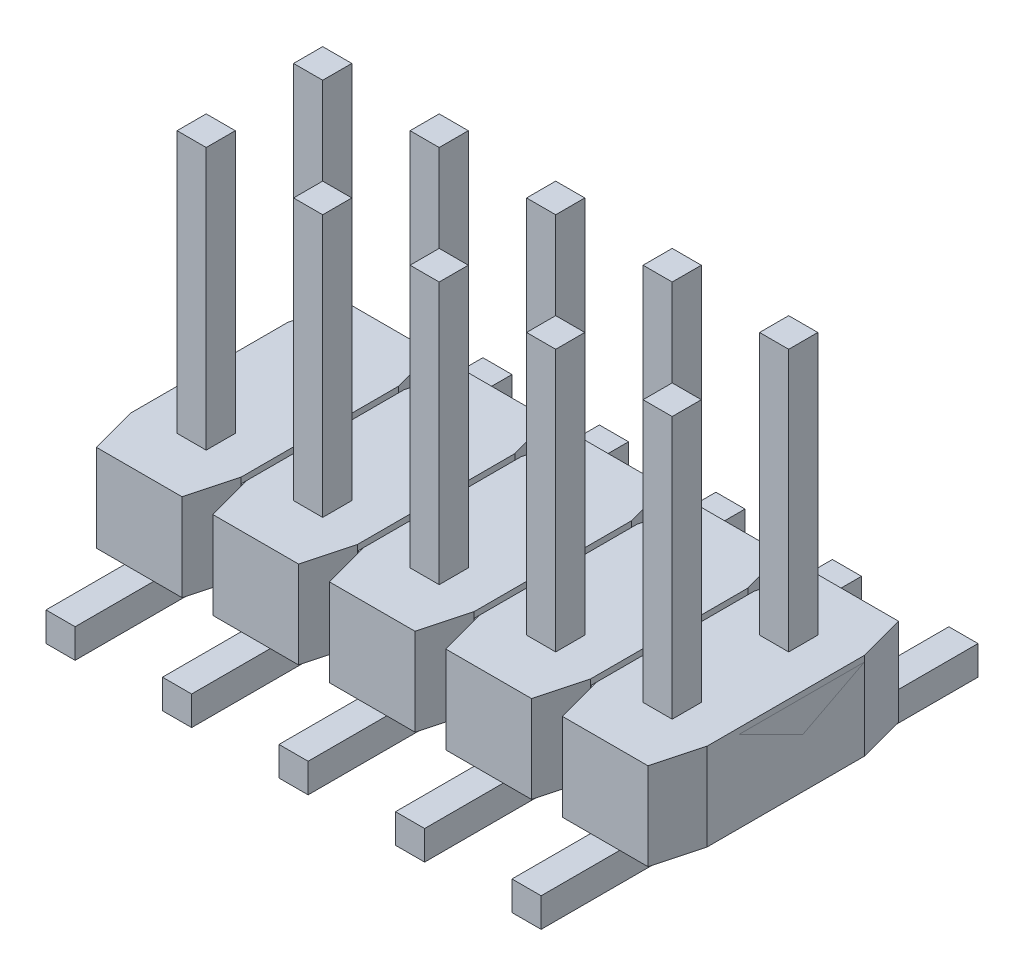
SolidWorks part; units mm, degrees
ref_plane "Alzado" through (0, 0, 0) normal (0, 0, 1) x (1, 0, 0)
ref_plane "Planta" through (0, 0, 0) normal (0, 1, 0) x (1, 0, 0)
ref_plane "Vista lateral" through (0, 0, 0) normal (1, 0, 0) x (0, 0, -1)
sketch "Croquis1" plane through (0, 0, 0) normal (0, 1, 0) x (1, 0, 0)
  line L0 (2, 0) -> (2.5, 0)
  line L1 (0, 0) -> (0.5, 0)
  line L2 (0, 0) -> (0, 0.5)
  line L3 (0, 0.5) -> (0.5, 0.5)
  line L4 (0.5, 0) -> (0.5, 0.5)
  line L5 (2, 0) -> (2, 0.5)
  line L6 (2, 0.5) -> (2.5, 0.5)
  line L7 (2.5, 0) -> (2.5, 0.5)
  line L8 (4, 0) -> (4.5, 0)
  line L9 (4, 0) -> (4, 0.5)
  line L10 (4, 0.5) -> (4.5, 0.5)
  line L11 (4.5, 0) -> (4.5, 0.5)
  line L12 (6, 0) -> (6.5, 0)
  line L13 (6, 0) -> (6, 0.5)
  line L14 (6, 0.5) -> (6.5, 0.5)
  line L15 (6.5, 0) -> (6.5, 0.5)
  line L16 (8, 0) -> (8.5, 0)
  line L17 (8, 0) -> (8, 0.5)
  line L18 (8, 0.5) -> (8.5, 0.5)
  line L19 (8.5, 0) -> (8.5, 0.5)
  line L80 (0, 2) -> (0.5, 2)
  line L81 (0, 2) -> (0, 2.5)
  line L82 (0, 2.5) -> (0.5, 2.5)
  line L83 (0.5, 2) -> (0.5, 2.5)
  line L84 (2, 2) -> (2.5, 2)
  line L85 (2, 2) -> (2, 2.5)
  line L86 (2, 2.5) -> (2.5, 2.5)
  line L87 (2.5, 2) -> (2.5, 2.5)
  line L88 (4, 2) -> (4.5, 2)
  line L89 (4, 2) -> (4, 2.5)
  line L90 (4, 2.5) -> (4.5, 2.5)
  line L91 (4.5, 2) -> (4.5, 2.5)
  line L92 (6, 2) -> (6.5, 2)
  line L93 (6, 2) -> (6, 2.5)
  line L94 (6, 2.5) -> (6.5, 2.5)
  line L95 (6.5, 2) -> (6.5, 2.5)
  line L96 (8, 2) -> (8.5, 2)
  line L97 (8, 2) -> (8, 2.5)
  line L98 (8, 2.5) -> (8.5, 2.5)
  line L99 (8.5, 2) -> (8.5, 2.5)
  line L160 (0, 0) -> (2, 0) construction
  line L161 (0, 0) -> (0, 2) construction
  dimension "D1" = 0.5
  dimension "D2" = 0.5
  dimension "D3" = 90
  dimension "D4" = 2
  dimension "D5" = 2
extrude "Extruir1" add sketch "Croquis1" along normal blind 6.5
sketch "Croquis2" plane through (0, 0, 0) normal (0, -1, 0) x (1, 0, 0)
  line L0 (2, 2.25) -> (2.5, 2.25)
  line L1 (0, 2.25) -> (0.5, 2.25)
  line L2 (0, 2.25) -> (0, -5.25)
  line L3 (0, -5.25) -> (0.5, -5.25)
  line L4 (0.5, 2.25) -> (0.5, -5.25)
  line L5 (2, 2.25) -> (2, -5.25)
  line L6 (2, -5.25) -> (2.5, -5.25)
  line L7 (2.5, 2.25) -> (2.5, -5.25)
  line L8 (4, 2.25) -> (4.5, 2.25)
  line L9 (4, 2.25) -> (4, -5.25)
  line L10 (4, -5.25) -> (4.5, -5.25)
  line L11 (4.5, 2.25) -> (4.5, -5.25)
  line L12 (6, 2.25) -> (6.5, 2.25)
  line L13 (6, 2.25) -> (6, -5.25)
  line L14 (6, -5.25) -> (6.5, -5.25)
  line L15 (6.5, 2.25) -> (6.5, -5.25)
  line L16 (8, 2.25) -> (8.5, 2.25)
  line L17 (8, 2.25) -> (8, -5.25)
  line L18 (8, -5.25) -> (8.5, -5.25)
  line L19 (8.5, 2.25) -> (8.5, -5.25)
  dimension "D1" = 7.5
  dimension "D2" = 0.5
  dimension "D3" = 2.25
  dimension "D4" = 2
extrude "Extruir2" add sketch "Croquis2" against normal blind 0.5
sketch "Croquis3" plane through (0, 0.5, 0) normal (0, 1, 0) x (-1, 0, 0)
  line L0 (-0.5, -5.25) -> (-0.5, -2.5) construction
  line L1 (-0.9856, -3.4) -> (0.4856, -3.4)
  line L2 (-1.2, -2.6) -> (-1.2, 0.1)
  line L3 (-0.9856, 0.9) -> (0.4856, 0.9)
  line L4 (0.7, -2.6) -> (0.7, 0.1)
  line L5 (0, -2.5) -> (0, -5.25) construction
  line L6 (-0.5, -2.5) -> (0, -2.5) construction
  line L7 (-0.5, 0) -> (0, 0) construction
  line L8 (-1.2, -2.6) -> (-0.9856, -3.4)
  line L9 (0.4856, -3.4) -> (0.7, -2.6)
  line L10 (0.4856, 0.9) -> (0.7, 0.1)
  line L11 (-1.2, 0.1) -> (-0.9856, 0.9)
  line L12 (-2.9856, -3.4) -> (-1.5144, -3.4)
  line L13 (-3.2, -2.6) -> (-3.2, 0.1)
  line L14 (-2.9856, 0.9) -> (-1.5144, 0.9)
  line L15 (-1.3, -2.6) -> (-1.3, 0.1)
  line L16 (-3.2, -2.6) -> (-2.9856, -3.4)
  line L17 (-1.5144, -3.4) -> (-1.3, -2.6)
  line L18 (-1.5144, 0.9) -> (-1.3, 0.1)
  line L19 (-3.2, 0.1) -> (-2.9856, 0.9)
  line L20 (-4.9856, -3.4) -> (-3.5144, -3.4)
  line L21 (-5.2, -2.6) -> (-5.2, 0.1)
  line L22 (-4.9856, 0.9) -> (-3.5144, 0.9)
  line L23 (-3.3, -2.6) -> (-3.3, 0.1)
  line L24 (-5.2, -2.6) -> (-4.9856, -3.4)
  line L25 (-3.5144, -3.4) -> (-3.3, -2.6)
  line L26 (-3.5144, 0.9) -> (-3.3, 0.1)
  line L27 (-5.2, 0.1) -> (-4.9856, 0.9)
  line L28 (-6.9856, -3.4) -> (-5.5144, -3.4)
  line L29 (-7.2, -2.6) -> (-7.2, 0.1)
  line L30 (-6.9856, 0.9) -> (-5.5144, 0.9)
  line L31 (-5.3, -2.6) -> (-5.3, 0.1)
  line L32 (-7.2, -2.6) -> (-6.9856, -3.4)
  line L33 (-5.5144, -3.4) -> (-5.3, -2.6)
  line L34 (-5.5144, 0.9) -> (-5.3, 0.1)
  line L35 (-7.2, 0.1) -> (-6.9856, 0.9)
  line L36 (-8.9856, -3.4) -> (-7.5144, -3.4)
  line L37 (-9.2, -2.6) -> (-9.2, 0.1)
  line L38 (-8.9856, 0.9) -> (-7.5144, 0.9)
  line L39 (-7.3, -2.6) -> (-7.3, 0.1)
  line L40 (-9.2, -2.6) -> (-8.9856, -3.4)
  line L41 (-7.5144, -3.4) -> (-7.3, -2.6)
  line L42 (-7.5144, 0.9) -> (-7.3, 0.1)
  line L43 (-9.2, 0.1) -> (-8.9856, 0.9)
  line L164 (-2.5, -2.5) -> (-2, -2.5)
  line L165 (-0.5, -2.5) -> (0, -2.5)
  line L166 (-0.5, -2.5) -> (-0.5, -2)
  line L167 (-0.5, -2) -> (0, -2)
  line L168 (0, -2.5) -> (0, -2)
  line L169 (-0.5, -0.5) -> (0, -0.5)
  line L170 (-0.5, -0.5) -> (-0.5, 0)
  line L171 (-0.5, 0) -> (0, 0)
  line L172 (0, -0.5) -> (0, 0)
  line L173 (-2.5, -2.5) -> (-2.5, -2)
  line L174 (-2.5, -2) -> (-2, -2)
  line L175 (-2, -2.5) -> (-2, -2)
  line L176 (-2.5, -0.5) -> (-2, -0.5)
  line L177 (-2.5, -0.5) -> (-2.5, 0)
  line L178 (-2.5, 0) -> (-2, 0)
  line L179 (-2, -0.5) -> (-2, 0)
  line L180 (-4.5, -2.5) -> (-4, -2.5)
  line L181 (-4.5, -2.5) -> (-4.5, -2)
  line L182 (-4.5, -2) -> (-4, -2)
  line L183 (-4, -2.5) -> (-4, -2)
  line L184 (-4.5, -0.5) -> (-4, -0.5)
  line L185 (-4.5, -0.5) -> (-4.5, 0)
  line L186 (-4.5, 0) -> (-4, 0)
  line L187 (-4, -0.5) -> (-4, 0)
  line L188 (-6.5, -2.5) -> (-6, -2.5)
  line L189 (-6.5, -2.5) -> (-6.5, -2)
  line L190 (-6.5, -2) -> (-6, -2)
  line L191 (-6, -2.5) -> (-6, -2)
  line L192 (-6.5, -0.5) -> (-6, -0.5)
  line L193 (-6.5, -0.5) -> (-6.5, 0)
  line L194 (-6.5, 0) -> (-6, 0)
  line L195 (-6, -0.5) -> (-6, 0)
  line L196 (-8.5, -2.5) -> (-8, -2.5)
  line L197 (-8.5, -2.5) -> (-8.5, -2)
  line L198 (-8.5, -2) -> (-8, -2)
  line L199 (-8, -2.5) -> (-8, -2)
  line L200 (-8.5, -0.5) -> (-8, -0.5)
  line L201 (-8.5, -0.5) -> (-8.5, 0)
  line L202 (-8.5, 0) -> (-8, 0)
  line L203 (-8, -0.5) -> (-8, 0)
  point P10 (-0.25, 0)
  point P15 (-1.2, -3.4)
  point P17 (0.7, -3.4)
  point P19 (0.7, 0.9)
  point P21 (-1.2, 0.9)
  point P27 (-3.2, 0.9)
  point P29 (-1.3, 0.9)
  point P31 (-1.3, -3.4)
  point P33 (-3.2, -3.4)
  point P39 (-5.2, 0.9)
  point P41 (-3.3, 0.9)
  point P43 (-3.3, -3.4)
  point P45 (-5.2, -3.4)
  point P51 (-7.2, 0.9)
  point P53 (-5.3, 0.9)
  point P55 (-5.3, -3.4)
  point P57 (-7.2, -3.4)
  point P63 (-9.2, 0.9)
  point P65 (-7.3, 0.9)
  point P67 (-7.3, -3.4)
  point P69 (-9.2, -3.4)
  dimension "D1" = 0.7
  dimension "D2" = 0.7
  dimension "D3" = 0.9
  dimension "D4" = 0.9
  dimension "D5" = 0.8
  dimension "D6" = 75
  dimension "D7" = 0.8
  dimension "D8" = 75
  dimension "D9" = 0.8
  dimension "D10" = 15
  dimension "D11" = 0.8
  dimension "D12" = 15
  dimension "D13" = 2
  dimension "D14" = 2
extrude "Extruir4" add sketch "Croquis3" along normal blind 1.5 separate body
sketch "Croquis4" plane through (0, 0.5, 0) normal (0, -1, 0) x (1, 0, 0)
  line L1 (9.2, 0.1) -> (-0.7, 0.1)
  line L2 (9.2, 0.1) -> (9.2, -2.6)
  line L3 (9.2, -2.6) -> (-0.7, -2.6)
  line L4 (-0.7, 0.1) -> (-0.7, -2.6)
extrude "Extruir5" add sketch "Croquis4" against normal blind 1.4 separate body
